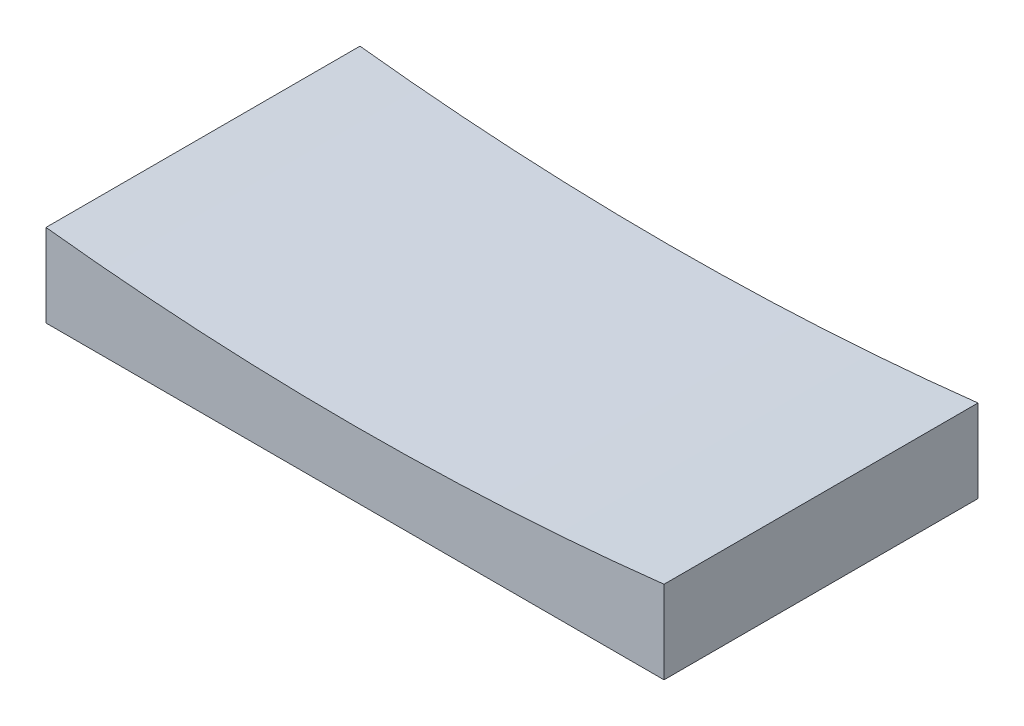
SolidWorks part; units mm, degrees
material "玻璃"
ref_plane "前视基准面" through (0, 0, 0) normal (0, 0, 1) x (1, 0, 0)
ref_plane "上视基准面" through (0, 0, 0) normal (0, 1, 0) x (1, 0, 0)
ref_plane "右视基准面" through (0, 0, 0) normal (1, 0, 0) x (0, 0, -1)
sketch "草图1" plane through (0, 0, 0) normal (0, 1, 0) x (1, 0, 0)
  line L0 (0, 18.6821) -> (0, -15.6404) construction
  line L1 (-25, 12.7) -> (25, 12.7)
  line L2 (-25, 12.7) -> (-25, -12.7)
  line L3 (-25, -12.7) -> (25, -12.7)
  line L4 (25, 12.7) -> (25, -12.7)
  line L5 (-19.3464, 0) -> (21.3545, 0) construction
  point P10 (-25, 0)
  point P11 (0, 12.7)
  dimension "D1" = 50
  dimension "D2" = 25.4
extrude "凸台-拉伸1" add sketch "草图1" along normal blind 6.7
sketch "草图2" plane through (0, 0, 12.7) normal (0, 0, 1) x (1, 0, 0)
  line L0 (-25, 1.7) -> (25, 1.7) construction
  line L1 (-25, 6.7) -> (-25, 0) construction
  line L2 (25, 6.7) -> (25, 0) construction
  line L3 (-25, 6.7) -> (25, 6.7) construction
  line L4 (0, 307.7666) -> (0, -18.6817) construction
  line L5 (-25, 0) -> (25, 0) construction
  line L6 (-25, 0) -> (25, 0)
  line L7 (25, 6.7) -> (25, 0)
  line L8 (-25, 6.7) -> (-25, 0)
  line L9 (-25, 6.7) -> (25, 6.7)
  arc A0 (-25, 6.7) -> (25, 6.7) centre (0, 225.2749) ccw
  point P8 (0, 1.7)
  point P12 (0, 225.2749)
  line M10 (25, 6.7) -> (-25, 6.7)
  line M11 (-25, 6.7) -> (-25, 0)
  dimension "D3" = 440
  dimension "D1" = 5
extrude "切除-拉伸1" cut sketch "草图2" against normal up to next contours A0 L7 M11 M10
